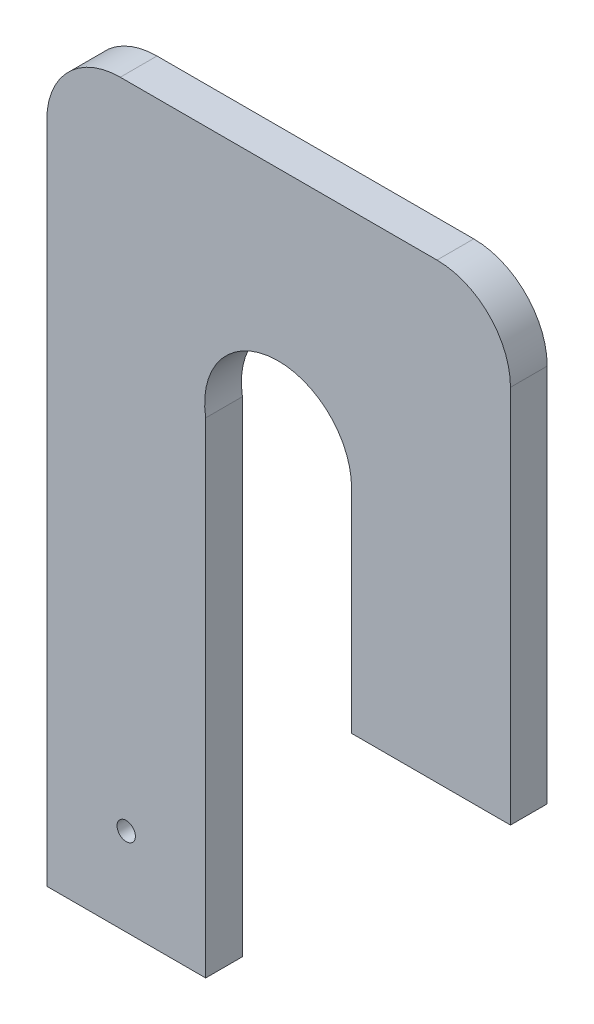
SolidWorks part; units mm, degrees
ref_plane "Front Plane" through (0, 0, 0) normal (0, 0, 1) x (1, 0, 0)
ref_plane "Top Plane" through (0, 0, 0) normal (0, 1, 0) x (1, 0, 0)
ref_plane "Right Plane" through (0, 0, 0) normal (1, 0, 0) x (0, 0, -1)
sketch "Sketch1" plane through (0, 0, 0) normal (0, 0, 1) x (1, 0, 0)
  line L0 (0, 167.706) -> (0, 0)
  line L1 (0, 0) -> (-54.9247, 0)
  line L4 (-54.9247, 254.9372) -> (105.3733, 254.9372)
  line L5 (105.3733, 254.9372) -> (105.3733, 173.0757)
  line L7 (-54.9247, 254.9372) -> (-54.9247, 0)
  line L11 (50.4486, 171.9164) -> (50.4486, 98.4645)
  line L12 (50.4486, 98.4645) -> (105.3733, 98.4645)
  line L13 (105.3733, 98.4645) -> (105.3733, 173.0757)
  arc A1 (0, 167.706) -> (50.4486, 171.9164) centre (25.0486, 171.9164) cw
  point P3 (-54.9247, 0)
  point P12 (25.2231, 169.8259)
extrude "Boss-Extrude2" add sketch "Sketch1" along normal blind 12.7
fillet "Fillet1" radius 25.4 1 edges at (-54.9247, 254.9372, 6.35)
fillet "Fillet2" radius 25.4 1 edges at (105.3733, 254.9372, 6.35)
sketch "Sketch3" plane through (0, 0, 12.7) normal (0, 0, 1) x (1, 0, 0)
  line L0 (-54.9247, 30.2624) -> (0, 30.2624) construction
  line L1 (-54.9247, 229.5372) -> (-54.9247, 0) construction
  line L2 (0, 0) -> (0, 167.706) construction
  circle A0 centre (-27.4624, 30.2624) radius 3.175
  point P8 (-27.4624, 30.2624)
  dimension "D1" = 6.35
extrude "Cut-Extrude3" cut sketch "Sketch3" against normal up to surface (12.7 mm away) up to face at (24.9955, 154.3439, 0)
